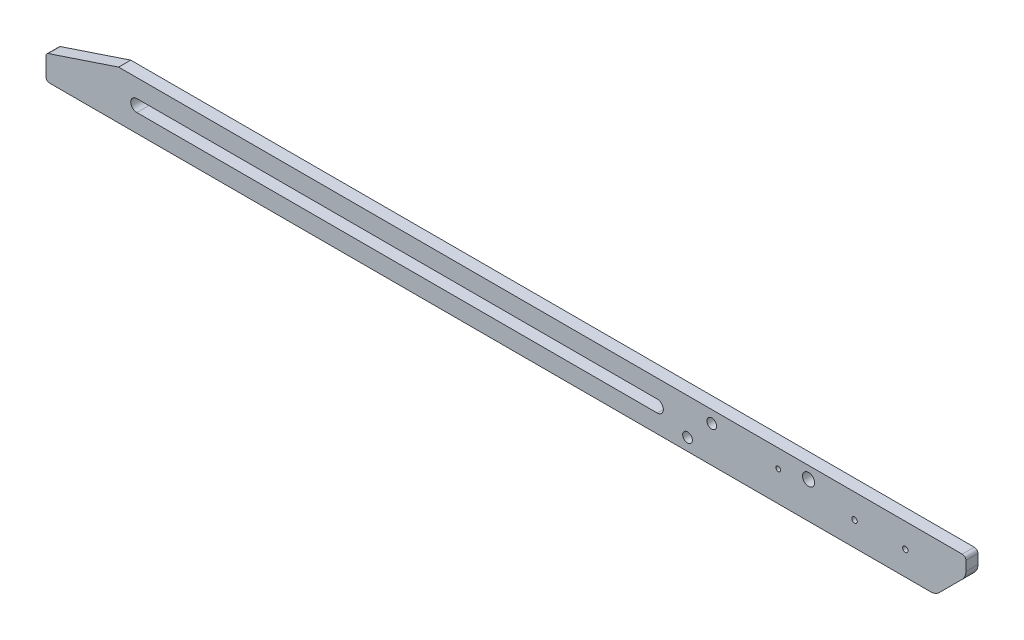
SolidWorks part; units mm, degrees
ref_plane "Plan de face" through (0, 0, 0) normal (0, 0, 1) x (1, 0, 0)
ref_plane "Plan de dessus" through (0, 0, 0) normal (0, 1, 0) x (1, 0, 0)
ref_plane "Plan de droite" through (0, 0, 0) normal (1, 0, 0) x (0, 0, -1)
sketch "Esquisse1" plane through (0, 0, 0) normal (0, 0, 1) x (1, 0, 0)
  line L1 (0, 0) -> (760, 0)
  line L2 (0, 0) -> (0, 40)
  line L3 (0, 40) -> (760, 40)
  line L4 (760, 0) -> (760, 40)
  dimension "D1" = 760
  dimension "D2" = 40
extrude "Boss.-Extru.1" add sketch "Esquisse1" along normal blind 10
sketch "Esquisse2" plane through (0, 0, 10) normal (0, 0, 1) x (1, 0, 0)
  line L0 (0, 40) -> (60, 40)
  line L1 (760, 40) -> (0, 40) construction
  line L2 (60, 40) -> (0, 20)
  line L3 (0, 40) -> (0, 0) construction
  line L4 (0, 20) -> (0, 40)
  dimension "D1" = 20
  dimension "D2" = 60
extrude "Enlèv. mat.-Extru.1" cut sketch "Esquisse2" against normal through all both and the other way through all
sketch "Esquisse3" plane through (0, 0, 10) normal (0, 0, 1) x (1, 0, 0)
  line L0 (290, 0) -> (290, 40) construction
  line L1 (0, 0) -> (760, 0) construction
  line L2 (760, 40) -> (60, 40) construction
  line L3 (290, 40) -> (290, 20) construction
  line L4 (75, 20) -> (505, 20) construction
  line L5 (75, 25) -> (505, 25)
  line L6 (75, 15) -> (505, 15)
  arc A0 (75, 25) -> (75, 15) centre (75, 20) ccw
  arc A1 (505, 15) -> (505, 25) centre (505, 20) ccw
  point P9 (290, 20)
  dimension "D1" = 10
  dimension "D2" = 290
  dimension "D3" = 430
  dimension "D4" = 20
extrude "Enlèv. mat.-Extru.2" cut sketch "Esquisse3" against normal through all both and the other way through all
sketch "Esquisse4" plane through (0, 0, 10) normal (0, 0, 1) x (1, 0, 0)
  line L0 (540, 0) -> (540, 40) construction
  line L1 (0, 0) -> (760, 0) construction
  line L2 (760, 40) -> (60, 40) construction
  line L3 (550, 30) -> (530, 10) construction
  line L4 (760, 0) -> (760, 40) construction
  circle A0 centre (530, 10) radius 4
  circle A1 centre (550, 30) radius 4
  point P8 (540, 20)
  dimension "D2" = 8
  dimension "D3" = 20
  dimension "D1" = 20
  dimension "D4" = 220
extrude "Enlèv. mat.-Extru.3" cut sketch "Esquisse4" against normal through all both and the other way through all
fillet "Congé1" radius 3 2 edges at (0, 0, 5) (0, 20, 5)
chamfer "Chanfrein1" distance 25 angle 45 1 edges at (760, 0, 5)
sketch "Esquisse5" plane through (0, 0, 10) normal (0, 0, 1) x (1, 0, 0)
  line L0 (626.6159, 0) -> (626.6159, 40) construction
  line L1 (3, 0) -> (735, 0) construction
  line L2 (760, 40) -> (60, 40) construction
  line L3 (626.6159, 20) -> (710, 20) construction
  line L4 (760, 25) -> (760, 40) construction
  circle A0 centre (710, 20) radius 2.25
  circle A1 centre (668, 20) radius 2.25
  circle A2 centre (630, 30) radius 5
  circle A3 centre (550, 30) radius 4 construction
  circle A4 centre (605, 25) radius 2
  dimension "D1" = 4.5
  dimension "D2" = 42
  dimension "D4" = 30
  dimension "D5" = 80
  dimension "D6" = 10
  dimension "D7" = 4
  dimension "D8" = 55
  dimension "D9" = 25
  dimension "D3" = 50
extrude "Enlèv. mat.-Extru.4" cut sketch "Esquisse5" against normal through all both and the other way through all
fillet "Congé2" radius 3 1 edges at (760, 40, 5)
fillet "Congé3" radius 10 2 edges at (735, 0, 5) (760, 25, 5)
